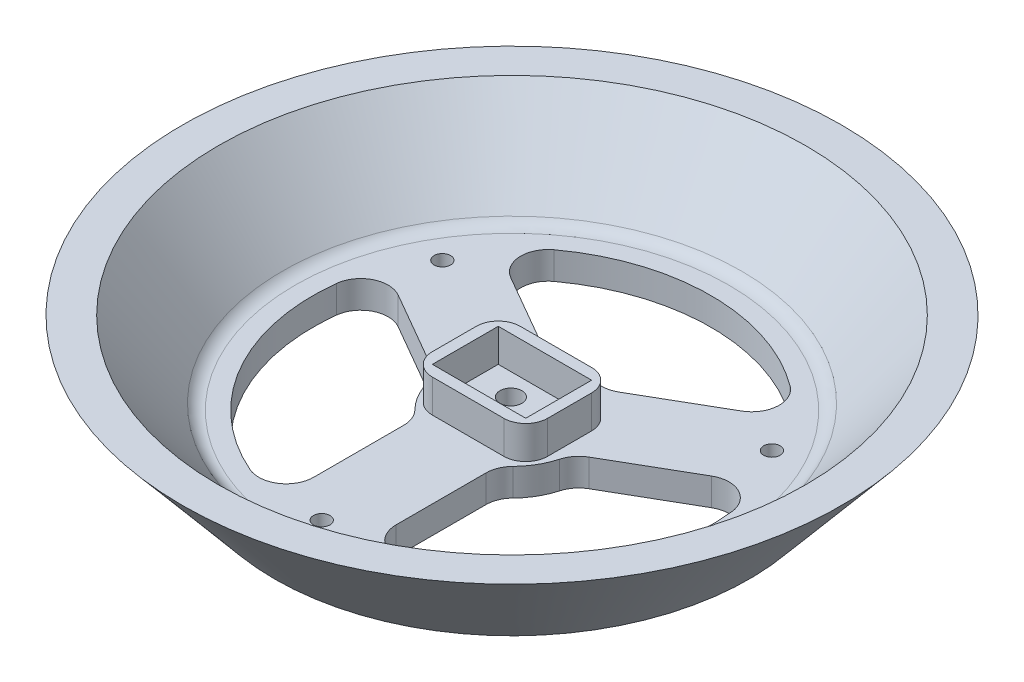
SolidWorks part; units mm, degrees
material "ABS"
ref_plane "Alzado" through (0, 0, 0) normal (0, 0, 1) x (1, 0, 0)
ref_plane "Planta" through (0, 0, 0) normal (0, 1, 0) x (1, 0, 0)
ref_plane "Vista lateral" through (0, 0, 0) normal (1, 0, 0) x (0, 0, -1)
sketch "Sketch1" plane through (0, 0, 0) normal (0, 1, 0) x (1, 0, 0)
  circle A0 centre (0, 0) radius 60
  dimension "D1" = 120
extrude "Boss-Extrude1" add sketch "Sketch1" against normal blind 20 draft 40
shell "Shell1" thickness 5
sketch "Sketch2" plane through (0, -20, 0) normal (0, -1, 0) x (1, 0, 0)
  line L0 (34.4358, -11.2213) -> (12.4103, 1.4952)
  line L2 (-7.5, 35.433) -> (-7.5, 10)
  line L4 (7.5, 35.433) -> (7.5, 10)
  line L6 (26.9358, -24.2117) -> (4.9103, -11.4952)
  line L8 (-26.9358, -24.2117) -> (-4.9103, -11.4952)
  line L10 (-34.4358, -11.2213) -> (-12.4103, 1.4952)
  line L11 (0, 0) -> (0, 36.218) construction
  line L12 (0, 0) -> (31.3657, -18.109) construction
  line L13 (0, 0) -> (-31.3657, -18.109) construction
  arc A0 (12.4103, 1.4952) -> (7.5, 10) centre (0, 0) ccw
  circle A1 centre (0, 0) radius 43.218 construction
  arc A3 (-4.9103, -11.4952) -> (4.9103, -11.4952) centre (0, 0) ccw
  arc A4 (-7.5, 10) -> (-12.4103, 1.4952) centre (0, 0) ccw
  circle A10 centre (0, 0) radius 36.218
  point P11 (0, 0)
  point P21 (0, 0)
  dimension "D1" = 25
  dimension "D7" = 7
  dimension "D2" = 15
  dimension "D4" = 7.5
  dimension "D5" = 7.5
  dimension "D6" = 7.5
  dimension "D3" = 3
  dimension "D9" = 3
extrude "Cut-Extrude2" cut sketch "Sketch2" against normal blind 20 contours L2 A10 L10 A4 | L0 A10 L4 A0 | L8 A10 L6 A3
sketch "Sketch3" plane through (0, -15, 0) normal (0, 1, 0) x (1, 0, 0)
  line L0 (-6.5, -8) -> (6.5, -8)
  line L1 (-8.5, 6) -> (8.5, 6)
  line L2 (-8.5, 6) -> (-8.5, -6)
  line L3 (-8.5, -6) -> (8.5, -6)
  line L4 (8.5, 6) -> (8.5, -6)
  line L5 (-8.5, 6) -> (8.5, -6) construction
  line L6 (-8.5, -6) -> (8.5, 6) construction
  line L7 (10.5, 4) -> (10.5, -4)
  line L8 (-6.5, 8) -> (6.5, 8)
  line L9 (-10.5, 4) -> (-10.5, -4)
  line L10 (-10.5, -8) -> (10.5, -8) construction
  line L11 (10.5, 8) -> (10.5, -8) construction
  line L12 (-10.5, 8) -> (10.5, 8) construction
  line L13 (-10.5, 8) -> (-10.5, -8) construction
  arc A0 (6.5, -8) -> (10.5, -4) centre (6.5, -4) ccw
  arc A1 (-6.5, 8) -> (-10.5, 4) centre (-6.5, 4) ccw
  arc A2 (-6.5, -8) -> (-10.5, -4) centre (-6.5, -4) cw
  arc A3 (10.5, 4) -> (6.5, 8) centre (6.5, 4) ccw
  point P0 (0, 0)
  dimension "D4" = 4
  dimension "D1" = 12
  dimension "D2" = 17
  dimension "D3" = 2
extrude "Boss-Extrude2" add sketch "Sketch3" along normal blind 6
hole_wizard "Ø3.0mm Dowel Hole1" positions "Sketch4" profile "Sketch6" hole size "Ø3.0" standard "ANSI Metric" end condition up to next
sketch "Sketch4" plane through (0, -15, 0) normal (0, 1, 0) x (1, 0, 0)
  line L1 (0, 0) -> (0, -40.8865) construction
  line L3 (0, 0) -> (-35.4087, 20.4432) construction
  line L4 (0, 0) -> (35.4087, 20.4432) construction
  circle A1 centre (0, 0) radius 40.8865 construction
  point P0 (-29.9991, 17.32)
  point P19 (29.9991, 17.32)
  point P20 (0, -34.64)
  dimension "D1" = 34.64
  dimension "D4" = 34.64
  dimension "D2" = 34.64
  dimension "D3" = 3
  dimension "D5" = 3
sketch "Sketch6" plane through (-29.9991, -15, -17.32) normal (1, 0, 0) x (0, 0, 1)
  line L0 (0, 0) -> (0, 5)
  line L1 (0, 5) -> (1.5, 5)
  line L2 (1.5, 5) -> (1.5, 0)
  line L5 (1.5, 0) -> (0, 0)
  line L11 (0, -6.35) -> (0, 107.95) construction
  dimension "Thru Hole Dia." = 3
  dimension "Thru Hole Depth" = 5
hole_wizard "Ø4.0mm Dowel Hole1" positions "Sketch8" profile "Sketch9" hole size "Ø4.0" standard "ANSI Metric" end condition up to next
sketch "Sketch8" plane through (0, -15, 0) normal (0, 1, 0) x (1, 0, 0)
  line L0 (-8.5, 6) -> (-8.5, -6) construction
  line L2 (8.5, 6) -> (-8.5, 6) construction
  point P0 (-2.2, 2)
  dimension "D1" = 6.3
  dimension "D2" = 4
sketch "Sketch9" plane through (-2.2, -15, -2) normal (1, 0, 0) x (0, 0, 1)
  line L0 (0, 0) -> (0, 5)
  line L1 (0, 5) -> (2, 5)
  line L2 (2, 5) -> (2, 0)
  line L5 (2, 0) -> (0, 0)
  line L11 (0, -6.35) -> (0, 107.95) construction
  dimension "Thru Hole Dia." = 4
  dimension "Thru Hole Depth" = 5
fillet "Fillet1" radius 5 12 edges at (-7.5, -17.5, 10) (-12.4103, -17.5, 1.4952) (-34.4358, -17.5, -11.2213) (-26.9358, -17.5, -24.2117) (26.9358, -17.5, -24.2117) (34.4358, -17.5, -11.2213) (7.5, -17.5, 35.433) (-7.5, -17.5, 35.433) (12.4103, -17.5, 1.4952) (7.5, -17.5, 10) (4.9103, -17.5, -11.4952) (-4.9103, -17.5, -11.4952)
fillet "Fillet2" radius 3 1 edges at (0, -15, 40.8865)
